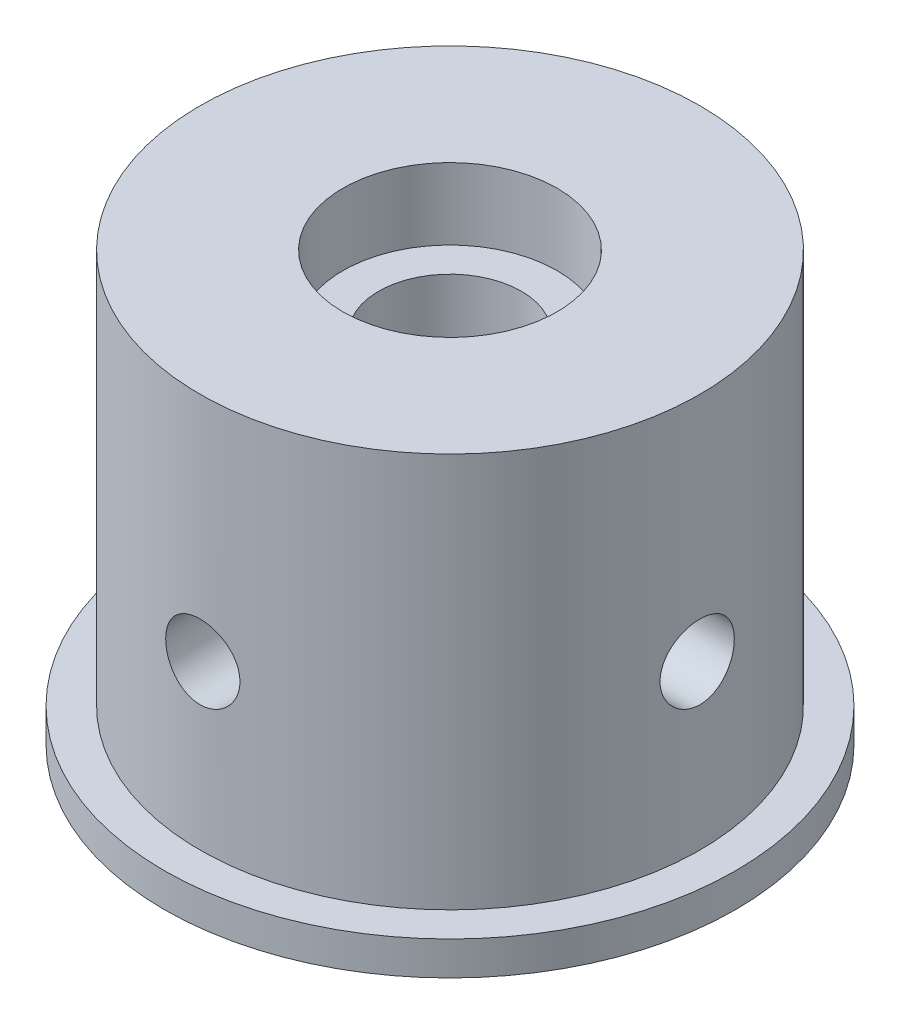
SolidWorks part; units mm, degrees
material "ABS"
ref_plane "Front Plane" through (0, 0, 0) normal (0, 0, 1) x (1, 0, 0)
ref_plane "Top Plane" through (0, 0, 0) normal (0, 1, 0) x (1, 0, 0)
ref_plane "Right Plane" through (0, 0, 0) normal (1, 0, 0) x (0, 0, -1)
sketch "Sketch1" plane through (0, 0, 0) normal (1, 0, 0) x (0, 0, -1)
  line L0 (-3.175, 0) -> (-4.7625, 0)
  line L1 (-4.7625, 0) -> (-4.7625, -3.175)
  line L2 (-4.7625, -3.175) -> (-12.7, -3.175)
  line L3 (-12.7, -3.175) -> (-12.7, -1.675)
  line L4 (-12.7, -1.675) -> (-11.1125, -1.675)
  line L5 (-11.1125, -1.675) -> (-11.1125, 15.875)
  line L6 (-11.1125, 15.875) -> (-4.7625, 15.875)
  line L7 (-4.7625, 15.875) -> (-4.7625, 12.7)
  line L8 (-4.7625, 12.7) -> (-3.175, 12.7)
  line L9 (-3.175, 12.7) -> (-3.175, 0)
  line L10 (0, -1000) -> (0, 49000) construction
  dimension "D1" = 12.7
  dimension "D2" = 11.1125
  dimension "D3" = 4.7625
  dimension "D4" = 12.7
  dimension "D5" = 3.175
  dimension "D6" = 3.175
  dimension "D7" = 1.5
revolve "Revolve1" add sketch "Sketch1" angle 360 about L10
sketch "Sketch2" plane through (0, 0, 0) normal (1, 0, 0) x (0, 0, -1)
  line L0 (12.7, -1.675) -> (-12.7, -1.675) construction
  circle A0 centre (0, 5.575) radius 1.65
  point P5 (0, 0)
  dimension "D1" = 3.3
  dimension "D2" = 7.25
extrude "Cut-Extrude1" cut sketch "Sketch2" against normal up to next from offset 5.5 offset against normal yes
pattern_circular "CirPattern1" count 4 over 360 about axis through (0, 0, 0) along (0, 1, 0) of "Cut-Extrude1"
